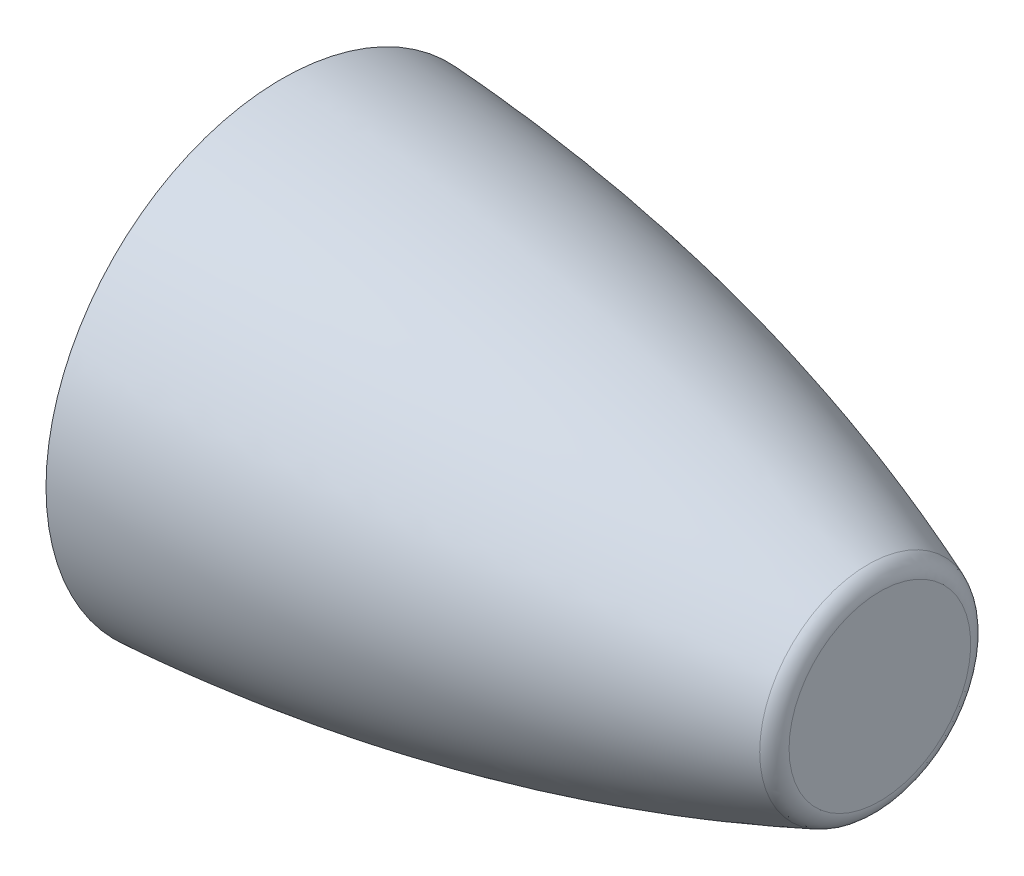
SolidWorks part; units mm, degrees
ref_plane "Plano frontal" through (0, 0, 0) normal (0, 0, 1) x (1, 0, 0)
ref_plane "Plano superior" through (0, 0, 0) normal (0, 1, 0) x (1, 0, 0)
ref_plane "Plano direito" through (0, 0, 0) normal (1, 0, 0) x (0, 0, -1)
ref_plane "Plano1" through (0, 0, 0) normal (0, 0, -1) x (-1, 0, 0)
sketch "Esboço1" plane through (0, 0, 0) normal (0, 0, -1) x (-1, 0, 0)
  line L0 (-15.875, 2.4102) -> (-15.875, 0)
  line L1 (-15.875, 0) -> (-12.7, 0)
  line L2 (-12.7, 0) -> (-12.7, 1.5875)
  line L3 (-12.7, 1.5875) -> (0, 1.5875)
  line L4 (0, 1.5875) -> (0, 6.2565)
  line L5 (-15.88, 0) -> (0, 0) construction
  spline S0 degree 3 poles (0, 6.2565) (-4.6091, 5.9844) (-10.0139, 5.0844) (-15.5601, 2.8747) knots 0 0 0 0 1 1 1 1
  spline S1 degree 3 poles (-15.875, 2.4102) (-15.875, 2.5973) (-15.7338, 2.8055) (-15.5601, 2.8747) knots 0 0 0 0 1 1 1 1
revolve "Revolução1" add sketch "Esboço1" angle 360 about L5
